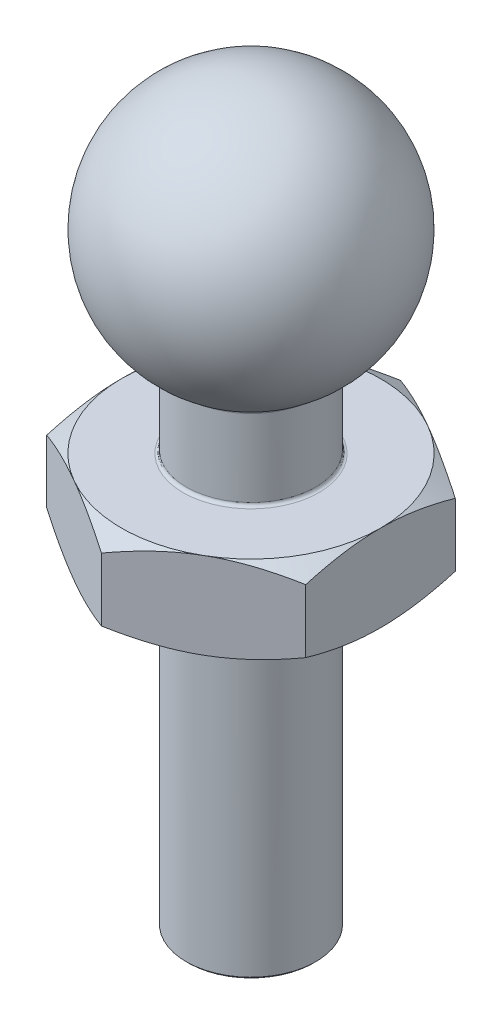
SolidWorks part; units mm, degrees
ref_plane "Front Plane" through (0, 0, 0) normal (0, 0, 1) x (1, 0, 0)
ref_plane "Top Plane" through (0, 0, 0) normal (0, 1, 0) x (1, 0, 0)
ref_plane "Right Plane" through (0, 0, 0) normal (1, 0, 0) x (0, 0, -1)
sketch "Sketch1" plane through (0, 0, 0) normal (0, 0, 1) x (1, 0, 0)
  line L1 (0, 0) -> (1.5, 0)
  line L2 (1.5, 0) -> (1.5, 11.4019)
  line L3 (0, 11) -> (0, 0)
  line L4 (0, 17) -> (0, 11)
  circle A0 centre (0, 14) radius 3 construction
  arc A1 (0, 17) -> (1.5, 11.4019) centre (0, 14) cw
  dimension "D1" = 6
  dimension "D2" = 1.5
  dimension "D3" = 11
revolve "Revolve1" add sketch "Sketch1" angle 360 about L3
sketch "Sketch2" plane through (0, 0, 0) normal (0, 0, 1) x (1, 0, 0)
  line L0 (-3.3659, 7.5) -> (3.0394, 7.5)
  dimension "D1" = 7.5
split line "Split Line1"
chamfer "Chamfer1" distance 0.05 angle 45 1 edges at (-1.5, 0, 0)
ref_plane "Plane2" through (0, 7.5, 0) normal (0, 1, 0) x (1, 0, 0)
sketch "Sketch6" plane through (0, 7.5, 0) normal (0, 1, 0) x (1, 0, 0)
  line L1 (3, 1.7321) -> (0, 3.4641)
  line L2 (0, 3.4641) -> (-3, 1.7321)
  line L3 (-3, 1.7321) -> (-3, -1.7321)
  line L4 (-3, -1.7321) -> (0, -3.4641)
  line L5 (0, -3.4641) -> (3, -1.7321)
  line L6 (3, -1.7321) -> (3, 1.7321)
  circle A0 centre (0, 0) radius 1.5
  circle A1 centre (0, 0) radius 3 construction
  circle A2 centre (0, 0) radius 1.5 construction
  dimension "D1" = 6
extrude "Boss-Extrude1" add sketch "Sketch6" along normal blind 2
sketch "Sketch7" plane through (0, 7.5, 0) normal (0, -1, 0) x (1, 0, 0)
  circle A0 centre (0, 0) radius 3 construction
  circle A1 centre (0, 0) radius 3
extrude "Cut-Extrude1" cut sketch "Sketch7" against normal blind 2 draft 60 flip side to cut
sketch "Sketch8" plane through (0, 9.5, 0) normal (0, 1, 0) x (1, 0, 0)
  circle A1 centre (0, 0) radius 3
  circle A2 centre (0, 0) radius 3
  dimension "D1" = 0
extrude "Cut-Extrude3" cut sketch "Sketch8" against normal blind 2 draft 60 flip side to cut
fillet "Fillet1" radius 0.075 2 edges at (-1.5, 11.4019, 0) (0, 9.5, 1.5)
